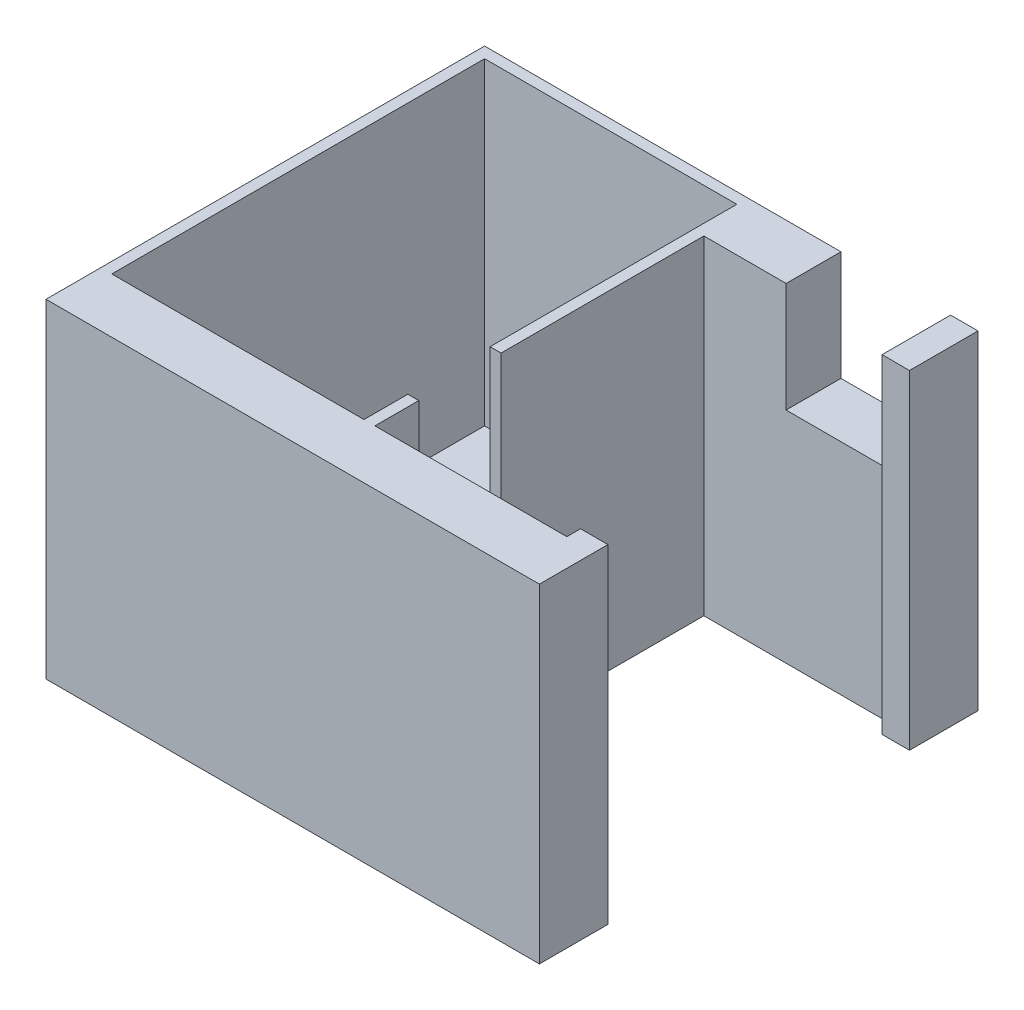
SolidWorks part; units mm, degrees
material "ABS"
ref_plane "Front Plane" through (0, 0, 0) normal (0, 0, 1) x (1, 0, 0)
ref_plane "Top Plane" through (0, 0, 0) normal (0, 1, 0) x (1, 0, 0)
ref_plane "Right Plane" through (0, 0, 0) normal (1, 0, 0) x (0, 0, -1)
sketch "Sketch1" plane through (0, 0, 0) normal (0, 1, 0) x (1, 0, 0)
  line L1 (-50.1969, 29.2715) -> (39.8031, 29.2715)
  line L2 (-50.1969, 29.2715) -> (-50.1969, -50.7285)
  line L3 (-50.1969, -50.7285) -> (39.8031, -50.7285)
  line L4 (39.8031, 29.2715) -> (39.8031, -50.7285)
  line L5 (-0.1969, 19.2715) -> (34.8031, 19.2715)
  line L6 (-0.1969, 19.2715) -> (-0.1969, -40.7285)
  line L7 (-0.1969, -40.7285) -> (34.8031, -40.7285)
  line L8 (34.8031, 19.2715) -> (34.8031, -40.7285)
  dimension "D1" = 90
  dimension "D2" = 80
  dimension "D3" = 5
  dimension "D4" = 10
  dimension "D5" = 10
  dimension "D6" = 35
extrude "Boss-Extrude1" add sketch "Sketch1" along normal blind 60
sketch "Sketch2" plane through (0, 60, 0) normal (0, 1, 0) x (1, 0, 0)
  line L0 (-50.1969, 29.2715) -> (-50.1969, -50.7285) construction
  line L1 (-2.1969, -40.7285) -> (-48.1969, -40.7285)
  line L2 (-2.1969, -40.7285) -> (-2.1969, 27.2715)
  line L3 (-2.1969, 27.2715) -> (-48.1969, 27.2715)
  line L4 (-48.1969, -40.7285) -> (-48.1969, 27.2715)
  line L5 (-50.1969, -50.7285) -> (39.8031, -50.7285) construction
  line L6 (-0.1969, 19.2715) -> (-0.1969, -40.7285) construction
  line L7 (39.8031, 29.2715) -> (-50.1969, 29.2715) construction
  dimension "D1" = 2
  dimension "D2" = 10
  dimension "D3" = 2
  dimension "D4" = 2
extrude "Cut-Extrude1" cut sketch "Sketch2" against normal offset from surface (58 mm away) 2 from surface at 0 up to face at (-5.1969, 0, 10.7285) starting at face at (-5.1969, 60, 10.7285)
sketch "Sketch3" plane through (-2.1969, 0, 0) normal (-1, 0, 0) x (0, 0, 1)
  line L0 (-27.2715, 60) -> (40.7285, 60) construction
  line L1 (32.7285, 60) -> (17.7285, 60)
  line L2 (32.7285, 60) -> (32.7285, 10)
  line L3 (32.7285, 10) -> (17.7285, 10)
  line L4 (17.7285, 60) -> (17.7285, 10)
  line L5 (40.7285, 2) -> (40.7285, 60) construction
  dimension "D1" = 15
  dimension "D2" = 50
  dimension "D3" = 8
extrude "Cut-Extrude2" cut sketch "Sketch3" against normal up to surface (2 mm away) up to face at (-0.1969, 30, 10.7285)
sketch "Sketch4" plane through (0, 0, -29.2715) normal (0, 0, -1) x (-1, 0, 0)
  line L0 (-39.8031, 60) -> (50.1969, 60) construction
  line L1 (-34.8031, 60) -> (-14.8031, 60)
  line L2 (-34.8031, 60) -> (-34.8031, 40)
  line L3 (-34.8031, 40) -> (-14.8031, 40)
  line L4 (-14.8031, 60) -> (-14.8031, 40)
  line L5 (-39.8031, 60) -> (-39.8031, 0) construction
  dimension "D1" = 20
  dimension "D2" = 20
  dimension "D3" = 5
extrude "Cut-Extrude3" cut sketch "Sketch4" against normal up to surface (10 mm away) up to face at (17.3031, 30, -19.2715)
sketch "Sketch5" plane through (39.8031, 0, 0) normal (1, 0, 0) x (0, 0, -1)
  line L0 (-50.7285, 60) -> (29.2715, 60) construction
  line L1 (-38.2285, 60) -> (16.7715, 60)
  line L2 (-38.2285, 60) -> (-38.2285, 0)
  line L3 (-38.2285, 0) -> (16.7715, 0)
  line L4 (16.7715, 60) -> (16.7715, 0)
  line L5 (44, 0) -> (-44, 0) construction
  line L6 (-50.7285, 60) -> (-50.7285, 0) construction
  dimension "D1" = 55
  dimension "D2" = 12.5
extrude "Cut-Extrude4" cut sketch "Sketch5" against normal blind 10
sketch "Sketch6" plane through (0, 0, 50.7285) normal (0, 0, 1) x (1, 0, 0)
  line L0 (-5.1969, 30) -> (39.8031, 30) construction
  line L1 (-50.1969, 60) -> (39.8031, 60) construction
  circle A0 centre (-5.1969, 30) radius 26
  dimension "D1" = 52
  dimension "D2" = 30
hole_wizard "CSK for M3 Flat Head Machine Screw1" positions "Sketch13" profile "Sketch14" countersink size "M3" standard "ANSI Metric"
sketch "Sketch13" plane through (0, 0, -29.2715) normal (0, 0, -1) x (-1, 0, 0)
  point P0 (5.1969, 30)
sketch "Sketch14" plane through (-5.1969, 30, -29.2715) normal (1, 0, 0) x (0, 1, 0)
  line L0 (0, 0) -> (0, 3.0815)
  line L1 (0, 3.0815) -> (1.8, 2)
  line L2 (1.8, 2) -> (1.8, 1.35)
  line L3 (1.8, 1.35) -> (3.15, 0)
  line L5 (3.15, 0) -> (0, 0)
  line L6 (-1.8, 1.35) -> (-3.15, 0) construction
  line L10 (0, 3.0815) -> (-1.8, 2) construction
  line L11 (0, -6.35) -> (0, 107.95) construction
  dimension "Hole Dia." = 3.6
  dimension "Hole Depth" = 2
  dimension "Near C'Sink Dia." = 6.3
  dimension "Near C'Sink Angle" = 90
  dimension "Drill Angle" = 118
